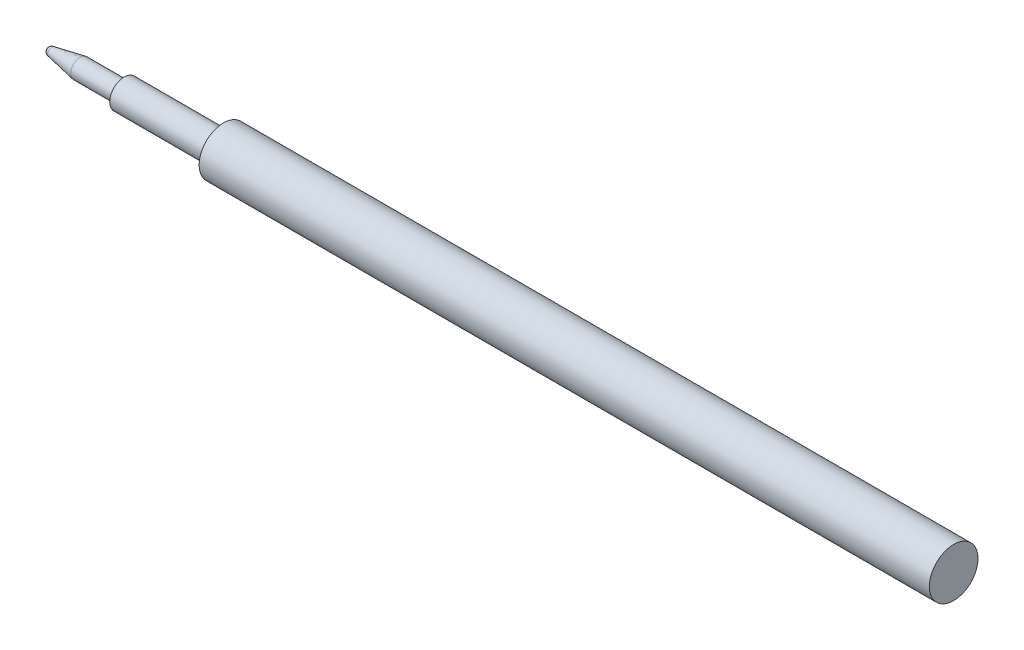
SolidWorks part; units mm, degrees
material "PP Film"
ref_plane "Front Plane" through (0, 0, 0) normal (0, 0, 1) x (1, 0, 0)
ref_plane "Top Plane" through (0, 0, 0) normal (0, 1, 0) x (1, 0, 0)
ref_plane "Right Plane" through (0, 0, 0) normal (1, 0, 0) x (0, 0, -1)
sketch "Sketch1" plane through (0, 0, 0) normal (0, 0, 1) x (1, 0, 0)
  line L0 (-90, 0) -> (-102.25, 0)
  line L1 (0, 0) -> (-90, 0)
  line L2 (0, 0) -> (0, 3)
  line L3 (0, 3) -> (-90, 3)
  line L4 (-90, 0) -> (-90, 3)
  line L5 (-102.25, 0) -> (-102.25, 1.77)
  line L6 (-102.25, 1.77) -> (-90, 1.77)
  line L7 (-102.25, 0) -> (-94.74, 0)
  line L10 (-94.74, 0) -> (-100.74, 0)
  line L13 (-100.74, 0) -> (-107.67, 0)
  line L14 (-107.67, 0) -> (-107.67, 1.16)
  line L15 (-107.67, 1.16) -> (-102.25, 1.16)
  line L16 (-107.67, 1.16) -> (-111.17, 0.5)
  line L17 (-111.17, 0.5) -> (-111.17, 0)
  line L18 (-111.17, 0) -> (-107.67, 0)
  line L19 (-111.17, 0) -> (-111.67, 0)
  arc A0 (-111.67, 0) -> (-111.17, 0.5) centre (-111.17, 0) cw
  dimension "D1" = 3
  dimension "D2" = 90
  dimension "D3" = 1.77
  dimension "D4" = 12.25
  dimension "D8" = 1.16
  dimension "D9" = 5.42
  dimension "D10" = 3.5
  dimension "D11" = 0.5
  dimension "D12" = 0.5
revolve "Revolve1" add sketch "Sketch1" angle 360 about L1
